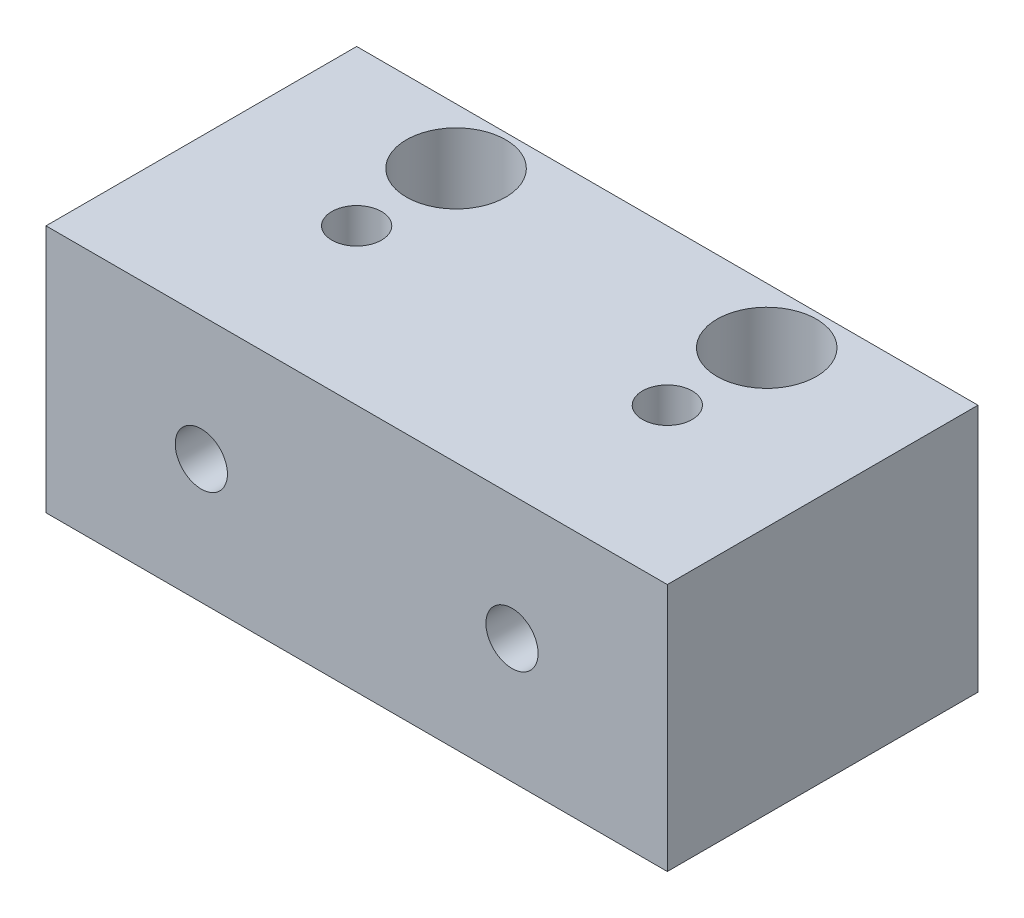
SolidWorks part; units mm, degrees
material "Polyetheretherketone (PEEK)"
ref_plane "Front Plane" through (0, 0, 0) normal (0, 0, 1) x (1, 0, 0)
ref_plane "Top Plane" through (0, 0, 0) normal (0, 1, 0) x (1, 0, 0)
ref_plane "Right Plane" through (0, 0, 0) normal (1, 0, 0) x (0, 0, -1)
ref_plane "Plane1" through (0, 10, 0) normal (0, 1, 0) x (1, 0, 0)
sketch "Sketch1" plane through (0, 10, 0) normal (0, 1, 0) x (1, 0, 0)
  line L0 (25, 0) -> (-25, 0)
  line L1 (-25, 0) -> (-25, -25)
  line L2 (-25, -25) -> (25, -25)
  line L3 (25, -25) -> (25, 0)
  dimension "D1" = 50
  dimension "D2" = 25
  dimension "D3" = 25
  dimension "D4" = 25
extrude "Boss-Extrude1" add sketch "Sketch1" against normal blind 20
hole_wizard "CBORE for M4 Hex Head Machine Screw1" positions "Sketch3" profile "Sketch2" counterbore size "M4" standard "ANSI Metric"
sketch "Sketch3" plane through (0, 10, 0) normal (0, 1, 0) x (1, 0, 0)
  point P0 (-12.5, -4.5)
  point P1 (12.5, -4.5)
  dimension "D1" = 12.5
  dimension "D2" = 4.5
  dimension "D3" = 12.5
  dimension "D4" = 4.5
sketch "Sketch2" plane through (-12.5, 10, 4.5) normal (1, 0, 0) x (0, 0, 1)
  line L0 (0, 0) -> (0, 20)
  line L1 (0, 20) -> (2.25, 20)
  line L3 (2.25, 20) -> (2.25, 6)
  line L4 (2.25, 6) -> (4, 6)
  line L5 (4, 6) -> (4, 0)
  line L7 (4, 0) -> (0, 0)
  line L11 (0, -6.35) -> (0, 107.95) construction
  dimension "Thru Hole Dia." = 4.5
  dimension "Thru Hole Depth" = 20
  dimension "C'Bore Dia." = 8
  dimension "C'Bore Depth" = 6
hole_wizard "Ø4.0 (4) Diameter Hole1" positions "Sketch5" profile "Sketch4" hole size "Ø4.0" standard "ANSI Metric"
sketch "Sketch5" plane through (0, 10, 0) normal (0, 1, 0) x (1, 0, 0)
  point P0 (-12.5, -12.5)
  point P1 (12.5, -12.5)
  dimension "D1" = 12.5
  dimension "D2" = 12.5
  dimension "D3" = 12.5
  dimension "D4" = 12.5
sketch "Sketch4" plane through (-12.5, 10, 12.5) normal (1, 0, 0) x (0, 0, 1)
  line L0 (0, 0) -> (0, 29.3597)
  line L1 (0, 29.3597) -> (2, 29.3597)
  line L2 (2, 29.3597) -> (2, 0)
  line L5 (2, 0) -> (0, 0)
  line L10 (0, 29.3597) -> (-2, 29.3597) construction
  line L11 (0, -6.35) -> (0, 107.95) construction
  dimension "Hole Dia." = 4
  dimension "Hole Depth" = 29.3597
  dimension "Drill Angle" = 180
hole_wizard "Ø4.2 (4.2) Diameter Hole1" positions "Sketch7" profile "Sketch6" hole size "Ø4.2" standard "ANSI Metric"
sketch "Sketch7" plane through (0, 0, 0) normal (0, 0, -1) x (-1, 0, 0)
  point P0 (12.5, 0)
  point P1 (-12.5, 0)
  dimension "D1" = 12.5
  dimension "D2" = 12.5
sketch "Sketch6" plane through (-12.5, 0, 0) normal (1, 0, 0) x (0, 1, 0)
  line L0 (0, 0) -> (0, 44.6922)
  line L1 (0, 44.6922) -> (2.1, 44.6922)
  line L2 (2.1, 44.6922) -> (2.1, 0)
  line L5 (2.1, 0) -> (0, 0)
  line L10 (0, 44.6922) -> (-2.1, 44.6922) construction
  line L11 (0, -6.35) -> (0, 107.95) construction
  dimension "Hole Dia." = 4.2
  dimension "Hole Depth" = 44.6922
  dimension "Drill Angle" = 180
